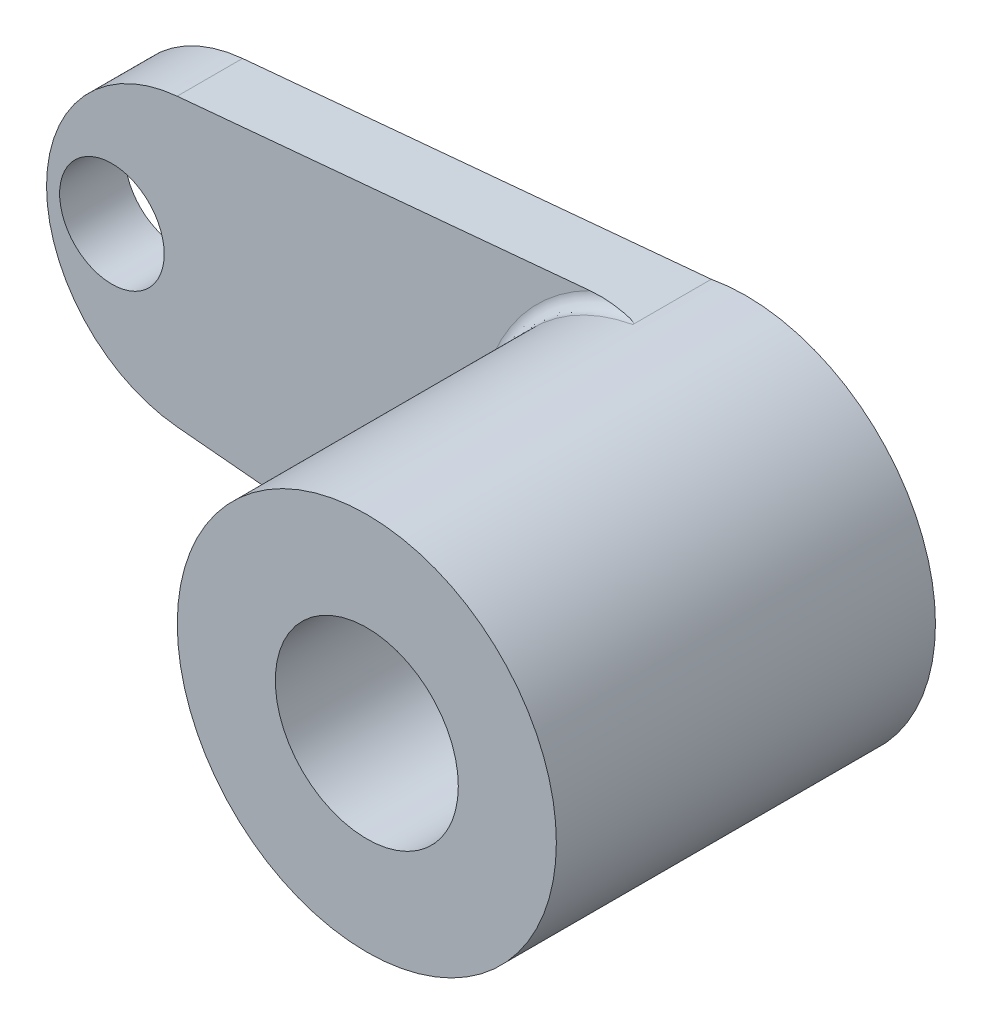
SolidWorks part; units mm, degrees
ref_plane "Front Plane" through (0, 0, 0) normal (0, 0, 1) x (1, 0, 0)
ref_plane "Top Plane" through (0, 0, 0) normal (0, 1, 0) x (1, 0, 0)
ref_plane "Right Plane" through (0, 0, 0) normal (1, 0, 0) x (0, 0, -1)
sketch "Sketch2" plane through (0, 0, 0) normal (0, 0, 1) x (1, 0, 0)
  circle A0 centre (0, 0) radius 14.5
  dimension "D1" = 29
extrude "Boss-Extrude1" add sketch "Sketch2" along normal blind 29
sketch "Sketch5" plane through (0, 0, 0) normal (0, 0, 1) x (1, 0, 0)
  line L0 (0, 14.5) -> (0, -14.5)
  line L1 (0, -14.5) -> (-38.5087, -10.9536)
  line L2 (-38.5087, 10.9536) -> (0, 14.5)
  line L3 (0, 0) -> (-60.826, 0) construction
  circle A0 centre (0, 0) radius 14.5 construction
  arc A1 (-38.5087, -10.9536) -> (-38.5087, 10.9536) centre (-37.5, 0) cw
  circle A2 centre (-43.5, 0) radius 4
  point P13 (-48.5, 0)
  dimension "D1" = 11
  dimension "D2" = 8
  dimension "D3" = 5
  dimension "D4" = 37.5
extrude "Boss-Extrude2" add sketch "Sketch5" along normal blind 5
fillet "Fillet1" radius 1 1 edges at (-14.5, 0, 5)
sketch "Sketch8" plane through (0, 0, 29) normal (0, 0, 1) x (1, 0, 0)
  circle A0 centre (0, 0) radius 7
  dimension "D1" = 14
extrude "Cut-Extrude1" cut sketch "Sketch8" against normal blind 25
cosmetic thread "Cosmetic Thread1" parameters "D2"=16
